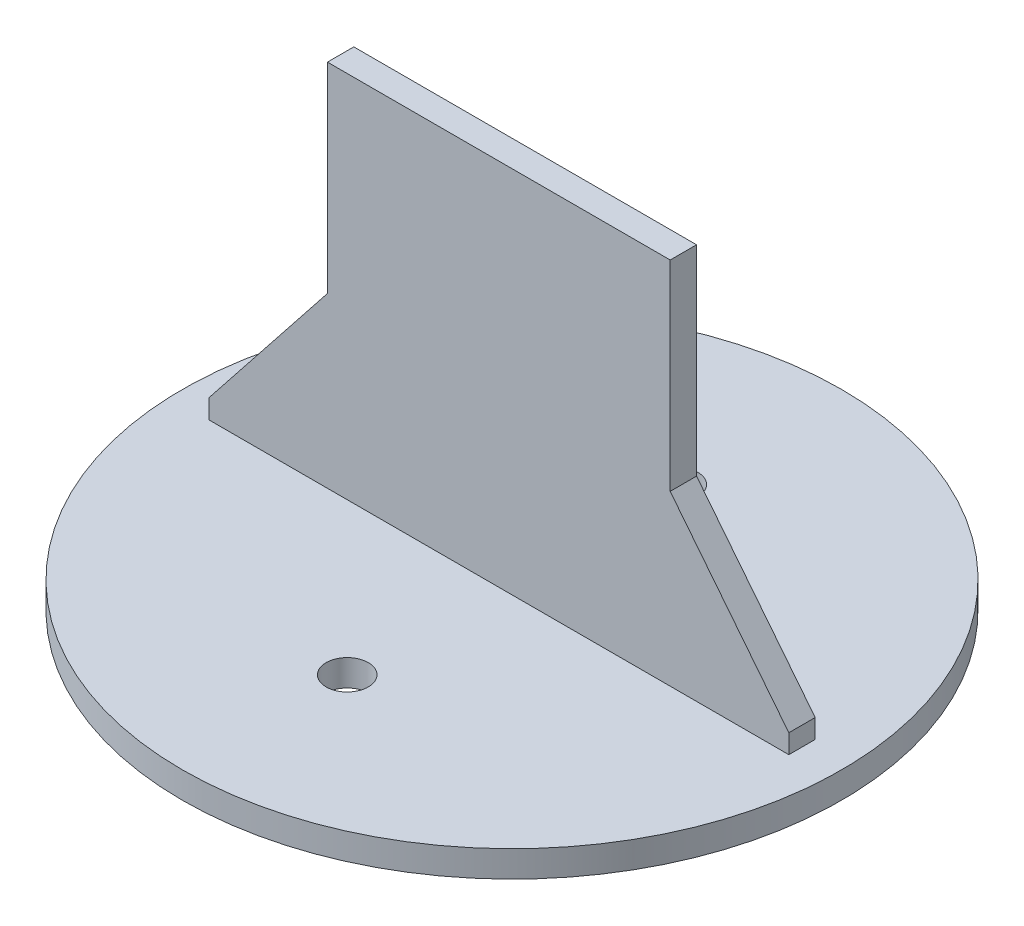
SolidWorks part; units mm, degrees
ref_plane "Front Plane" through (0, 0, 0) normal (0, 0, 1) x (1, 0, 0)
ref_plane "Top Plane" through (0, 0, 0) normal (0, 1, 0) x (1, 0, 0)
ref_plane "Right Plane" through (0, 0, 0) normal (1, 0, 0) x (0, 0, -1)
sketch "Sketch1" plane through (0, 0, 0) normal (0, 1, 0) x (1, 0, 0)
  circle A0 centre (0, 0) radius 12.5
  circle A1 centre (0, 6.25) radius 0.8
  circle A2 centre (0, -6.25) radius 0.8
  dimension "D1" = 6.25
  dimension "D2" = 6.25
extrude "Boss-Extrude1" add sketch "Sketch1" against normal blind 1
sketch "Sketch2" plane through (0, 0, 0) normal (0, 0, 1) x (1, 0, 0)
  line L0 (-11, 0) -> (-11, 0.7212)
  line L1 (12.5, 0) -> (-12.5, 0) construction
  line L2 (-11, 0.7212) -> (-6.5, 6.4)
  line L3 (-6.5, 6.4) -> (-6.5, 14)
  line L4 (-6.5, 14) -> (6.5, 14)
  line L6 (11, 0) -> (-11, 0)
  line L8 (6.5, 6.4) -> (6.5, 14)
  line L9 (11, 0.7212) -> (6.5, 6.4)
  line L10 (11, 0) -> (11, 0.7212)
  dimension "D3" = 14
  dimension "D4" = 7.6
extrude "Boss-Extrude2" add sketch "Sketch2" along normal mid plane 1
